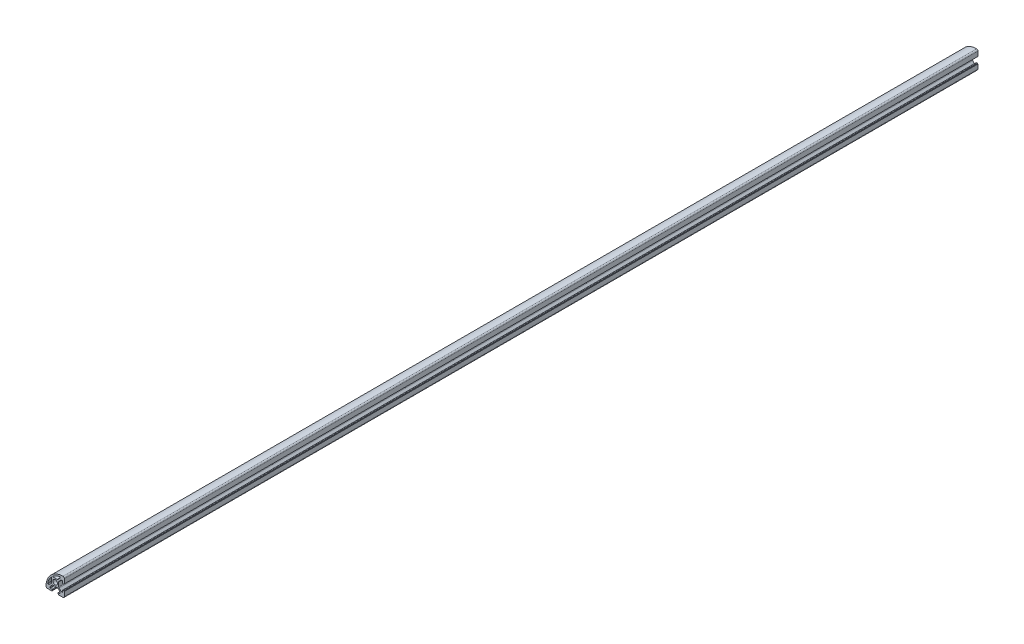
SolidWorks part; units mm, degrees
ref_plane "前视基准面" through (0, 0, 0) normal (0, 0, 1) x (1, 0, 0)
ref_plane "上视基准面" through (0, 0, 0) normal (0, 1, 0) x (1, 0, 0)
ref_plane "右视基准面" through (0, 0, 0) normal (1, 0, 0) x (0, 0, -1)
sketch "草图1" plane through (0, 0, 0) normal (0, 0, 1) x (1, 0, 0)
  line L0 (4.216, 3.1292) -> (6.4367, 5.3498)
  line L1 (6.4367, 5.3498) -> (7.7767, 5.3498)
  line L2 (8.0767, 5.0498) -> (8.0767, 3.2498)
  line L3 (8.3767, 2.9498) -> (9.3767, 2.9498)
  line L4 (9.3767, 2.9498) -> (9.3767, 3.2498)
  line L5 (9.5767, 3.4498) -> (9.9921, 3.4498)
  line L6 (9.9921, 3.4498) -> (9.9921, 8.4652)
  line L12 (5.3767, 7.8649) -> (5.3767, 6.5249)
  line L13 (5.3767, 6.5249) -> (3.156, 4.3042)
  line L14 (2.0953, 3.8649) -> (-2.342, 3.8649)
  line L29 (-4.0233, 2.1836) -> (-4.0233, -2.2538)
  line L30 (-4.4627, -3.3144) -> (-6.6833, -5.5351)
  line L31 (-6.6833, -5.5351) -> (-8.0233, -5.5351)
  line L37 (-8.6233, -10.1502) -> (-3.7233, -10.1502)
  line L38 (-3.7233, -10.1502) -> (-3.7233, -9.8502)
  line L39 (-3.5233, -9.6502) -> (-3.2233, -9.6502)
  line L40 (-3.2233, -9.6502) -> (-3.2233, -8.6502)
  line L41 (-3.5233, -8.3502) -> (-5.3233, -8.3502)
  line L42 (-5.6233, -8.0502) -> (-5.6233, -6.7102)
  line L43 (-5.6233, -6.7102) -> (-3.4027, -4.4895)
  line L44 (-2.342, -4.0502) -> (2.0953, -4.0502)
  line L45 (3.156, -4.4895) -> (5.3767, -6.7102)
  line L46 (5.3767, -6.7102) -> (5.3767, -8.0502)
  line L47 (5.0767, -8.3502) -> (3.2767, -8.3502)
  line L48 (2.9767, -8.6502) -> (2.9767, -9.6502)
  line L49 (2.9767, -9.6502) -> (3.2767, -9.6502)
  line L50 (3.4767, -9.8502) -> (3.4767, -10.1502)
  line L51 (3.4767, -10.1502) -> (8.3767, -10.1502)
  line L52 (9.8767, -8.6502) -> (9.8767, -3.7502)
  line L53 (9.8767, -3.7502) -> (9.5767, -3.7502)
  line L54 (9.3767, -3.5502) -> (9.3767, -3.2502)
  line L55 (9.3767, -3.2502) -> (8.3767, -3.2502)
  line L56 (8.0767, -3.5502) -> (8.0767, -5.3502)
  line L57 (7.7767, -5.6502) -> (6.4367, -5.6502)
  line L58 (6.4367, -5.6502) -> (4.216, -3.4295)
  line L59 (3.7767, -2.3689) -> (3.7767, 2.0685)
  circle A0 centre (-0.1233, -0.0351) radius 2.5
  arc A1 (8.0767, 5.0498) -> (7.7767, 5.3498) centre (7.7767, 5.0498) ccw
  arc A2 (8.0767, 3.2498) -> (8.3767, 2.9498) centre (8.3767, 3.2498) ccw
  arc A3 (9.5767, 3.4498) -> (9.3767, 3.2498) centre (9.5767, 3.2498) ccw
  arc A4 (9.9921, 8.4652) -> (8.4921, 9.9652) centre (8.4921, 8.4652) ccw
  arc A8 (2.0953, 3.8649) -> (3.156, 4.3042) centre (2.0953, 5.3649) ccw
  arc A9 (-3.0267, 4.0303) -> (-2.342, 3.8649) centre (-2.342, 5.3649) ccw
  arc A10 (-3.0267, 4.0303) -> (5.3767, 7.8649) centre (7.6364, -8.2121) cw
  arc A17 (-4.0233, 2.1836) -> (-4.2034, 2.8962) centre (-5.5233, 2.1836) ccw
  arc A18 (-4.4627, -3.3144) -> (-4.0233, -2.2538) centre (-5.5233, -2.2538) ccw
  arc A19 (-8.3233, -5.2351) -> (-8.0233, -5.5351) centre (-8.0233, -5.2351) ccw
  arc A22 (-10.1233, -8.6502) -> (-8.6233, -10.1502) centre (-8.6233, -8.6502) ccw
  arc A23 (-3.5233, -9.6502) -> (-3.7233, -9.8502) centre (-3.5233, -9.8502) ccw
  arc A24 (-3.2233, -8.6502) -> (-3.5233, -8.3502) centre (-3.5233, -8.6502) ccw
  arc A25 (-5.6233, -8.0502) -> (-5.3233, -8.3502) centre (-5.3233, -8.0502) ccw
  arc A26 (-2.342, -4.0502) -> (-3.4027, -4.4895) centre (-2.342, -5.5502) ccw
  arc A27 (3.156, -4.4895) -> (2.0953, -4.0502) centre (2.0953, -5.5502) ccw
  arc A28 (5.0767, -8.3502) -> (5.3767, -8.0502) centre (5.0767, -8.0502) ccw
  arc A29 (3.2767, -8.3502) -> (2.9767, -8.6502) centre (3.2767, -8.6502) ccw
  arc A30 (3.4767, -9.8502) -> (3.2767, -9.6502) centre (3.2767, -9.8502) ccw
  arc A31 (8.3767, -10.1502) -> (9.8767, -8.6502) centre (8.3767, -8.6502) ccw
  arc A32 (9.3767, -3.5502) -> (9.5767, -3.7502) centre (9.5767, -3.5502) ccw
  arc A33 (8.3767, -3.2502) -> (8.0767, -3.5502) centre (8.3767, -3.5502) ccw
  arc A34 (7.7767, -5.6502) -> (8.0767, -5.3502) centre (7.7767, -5.3502) ccw
  arc A35 (3.7767, -2.3689) -> (4.216, -3.4295) centre (5.2767, -2.3689) ccw
  arc A36 (4.216, 3.1292) -> (3.7767, 2.0685) centre (5.2767, 2.0685) ccw
  arc A37 (8.4921, 9.9652) -> (-10.1233, -8.6502) centre (8.4921, -8.6502) ccw
  arc A38 (-8.3233, -5.2351) -> (-4.2034, 2.8962) centre (7.6364, -8.2121) cw
extrude "凸台-拉伸1" add sketch "草图1" along normal blind 1000
